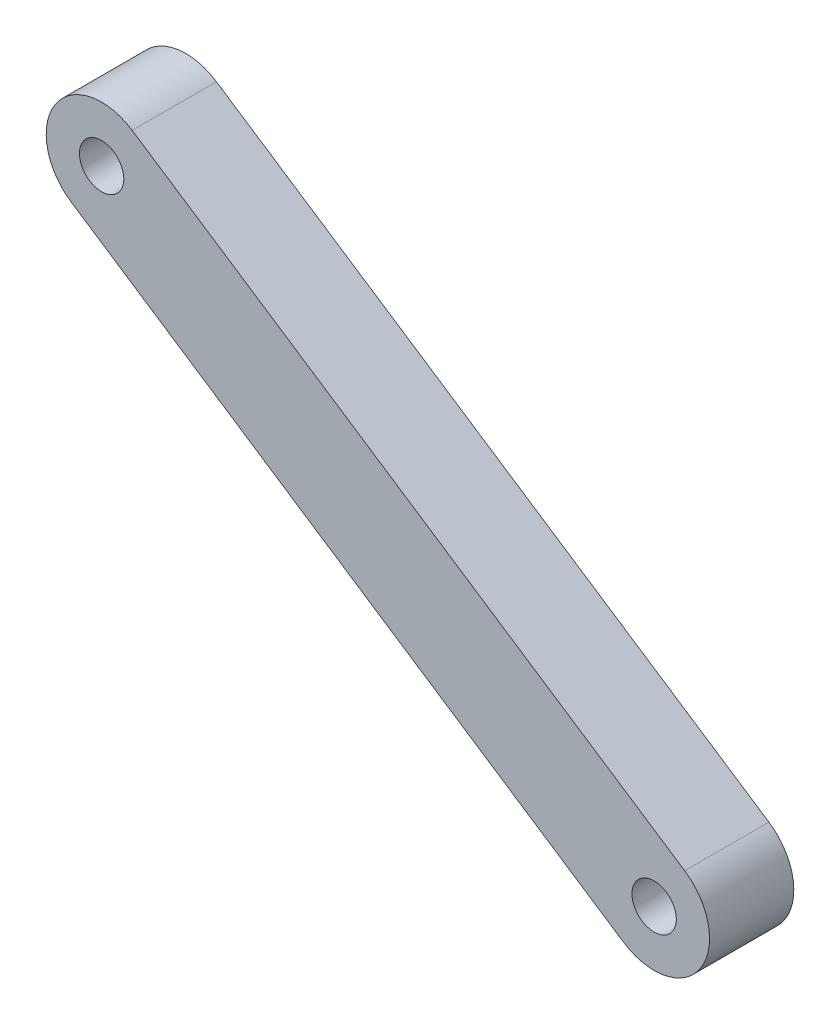
SolidWorks part; units mm, degrees
ref_plane "Спереди" through (0, 0, 0) normal (0, 0, 1) x (1, 0, 0)
ref_plane "Сверху" through (0, 0, 0) normal (0, 1, 0) x (1, 0, 0)
ref_plane "Справа" through (0, 0, 0) normal (1, 0, 0) x (0, 0, -1)
sketch "Sketch1" plane through (0, 0, 0) normal (0, 0, 1) x (1, 0, 0)
  line L0 (-17.1608, 49.3029) -> (7.7617, 32.8409) construction
  line L5 (-15.7829, 51.3889) -> (9.1396, 34.9269)
  line L6 (-18.5387, 47.2168) -> (6.3839, 30.7549)
  line L32 (7.7617, 32.8409) -> (-17.1608, 49.3029) construction
  circle A1 centre (-17.1608, 49.3029) radius 1
  circle A2 centre (7.7617, 32.8409) radius 1
  arc A3 (-15.7829, 51.3889) -> (-18.5387, 47.2168) centre (-17.1608, 49.3029) ccw
  arc A4 (6.3839, 30.7549) -> (9.1396, 34.9269) centre (7.7617, 32.8409) ccw
  point P1 (-4.6995, 41.0719)
  dimension "D5" = 2
  dimension "D3" = 2.5
  dimension "D1" = 5
  dimension "D2" = 5
extrude "Boss-Extrude1" add sketch "Sketch1" along normal blind 3.8
ref_plane "Plane1" through (17.4607, 26.4345, 0) normal (0.5511, 0.8344, 0) x (0.8344, -0.5511, 0)
